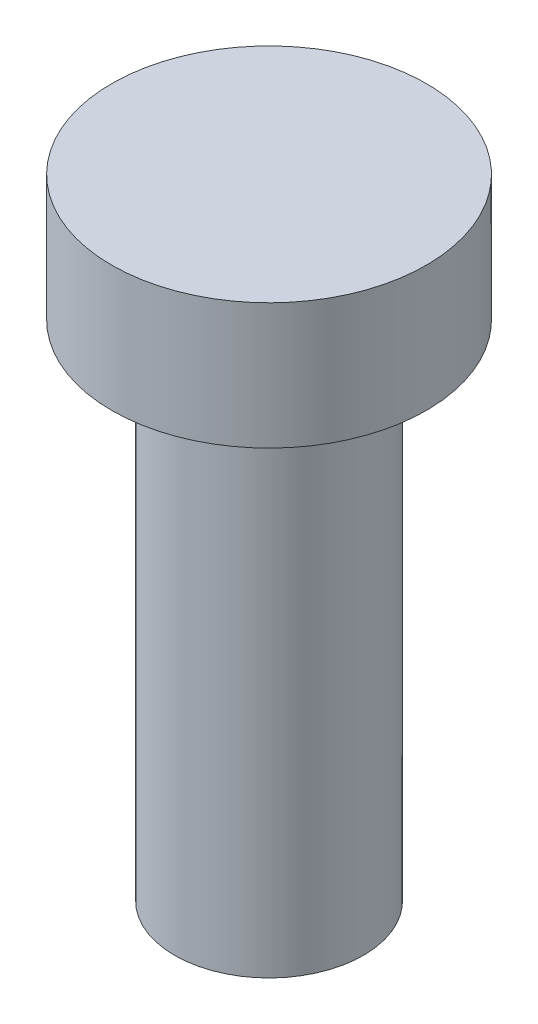
SolidWorks part; units mm, degrees
ref_plane "Front Plane" through (0, 0, 0) normal (0, 0, 1) x (1, 0, 0)
ref_plane "Top Plane" through (0, 0, 0) normal (0, 1, 0) x (1, 0, 0)
ref_plane "Right Plane" through (0, 0, 0) normal (1, 0, 0) x (0, 0, -1)
sketch "Sketch1" plane through (0, 0, 0) normal (0, 1, 0) x (1, 0, 0)
  circle A0 centre (0, 0) radius 1.5
  dimension "D1" = 3
extrude "Boss-Extrude1" add sketch "Sketch1" along normal blind 8
sketch "Sketch2" plane through (0, 8, 0) normal (0, 1, 0) x (1, 0, 0)
  circle A0 centre (0, 0) radius 2.5
  dimension "D1" = 5
extrude "Boss-Extrude2" add sketch "Sketch2" along normal blind 2
